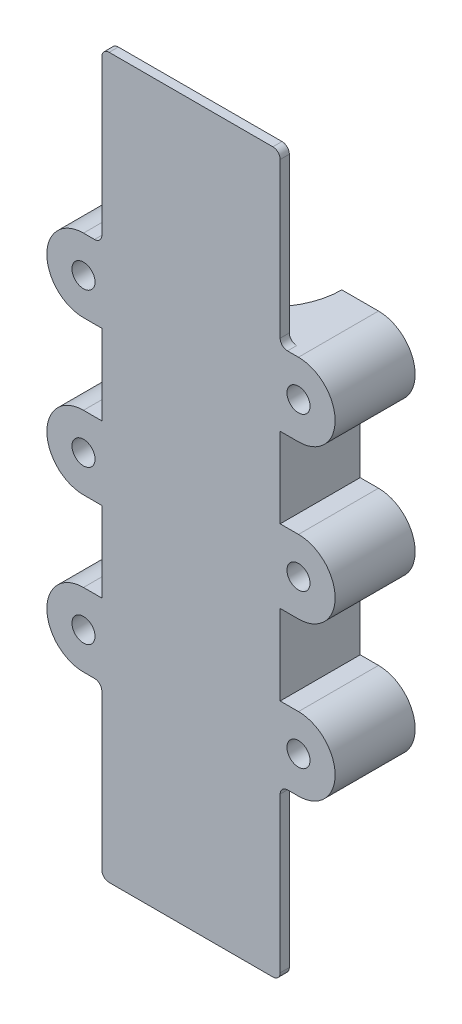
SolidWorks part; units mm, degrees
material "ABS"
ref_plane "X-Y Datum" through (0, 0, 0) normal (0, 0, 1) x (1, 0, 0)
ref_plane "X-Z Datum" through (0, 0, 0) normal (0, 1, 0) x (1, 0, 0)
ref_plane "Y-Z Datum" through (0, 0, 0) normal (1, 0, 0) x (0, 0, -1)
sketch "Sketch1" plane through (0, 0, 0) normal (0, 1, 0) x (1, 0, 0)
  line L0 (-12.2809, 0) -> (-15.4559, 0)
  line L1 (12.2809, 0) -> (15.4559, 0)
  line L4 (-15.4559, -13.3604) -> (-15.4559, 0)
  line L5 (15.4559, 0) -> (15.4559, -13.3604)
  line L10 (0, -13.8684) -> (15.4559, -13.8684)
  line L11 (15.4559, -13.8684) -> (15.4559, -13.3604)
  line L12 (-15.4559, -13.3604) -> (-15.4559, -13.8684)
  line L13 (-15.4559, -13.8684) -> (0, -13.8684)
  arc A0 (-12.2809, 0) -> (12.2809, 0) centre (0, 0) ccw
extrude "Boss-Extrude1" add sketch "Sketch1" along normal blind 65.8876
sketch "Sketch2" plane through (0, 65.8876, 0) normal (0, 1, 0) x (1, 0, 0)
  line L2 (-12.2809, -12.2809) -> (0, -12.2809)
  line L3 (0, -12.2809) -> (12.2809, -12.2809)
  line L6 (15.4559, -12.2809) -> (15.4559, -13.3604)
  line L8 (-15.4559, -13.3604) -> (-15.4559, -12.2809)
  line L9 (-12.2809, -12.2809) -> (-15.4559, -12.2809)
  line L10 (12.2809, -12.2809) -> (15.4559, -12.2809)
  line L13 (-15.4559, -13.3604) -> (-15.4559, -13.8684)
  line L14 (-15.4559, -13.8684) -> (15.4559, -13.8684)
  line L15 (15.4559, -13.8684) -> (15.4559, -13.3604)
  arc A0 (-12.2809, 0) -> (12.2809, 0) centre (0, 0) ccw construction
  point P0 (0, 0)
extrude "Boss-Extrude2" add sketch "Sketch2" along normal blind 29.3624
ref_plane "Plane1" through (0, 32.9438, 0) normal (0, 1, 0) x (1, 0, 0)
mirror "Mirror1" about plane through (0, 32.9438, 0) normal (0, 1, 0) of "Boss-Extrude2"
sketch "Sketch4" plane through (0, 0, 0) normal (0, 0, -1) x (-1, 0, 0)
  line L0 (-15.4559, 39.2938) -> (-15.4559, 26.5938)
  line L1 (-15.4559, 0) -> (-15.4559, 3.175) construction
  line L2 (8.5007, 32.9438) -> (-8.5007, 32.9438) construction
  line L3 (-18.6309, 39.2938) -> (-15.4559, 39.2938)
  line L4 (-18.6309, 26.5938) -> (-15.4559, 26.5938)
  line L5 (-15.4559, 65.8876) -> (-15.4559, 62.7126) construction
  line L6 (-15.4559, 65.8876) -> (-15.4559, 0) construction
  line L7 (-15.4559, 12.7) -> (-18.6309, 12.7)
  line L8 (-15.4559, 0) -> (-15.4559, 12.7)
  line L9 (-18.6309, 65.8876) -> (-15.4559, 65.8876)
  line L10 (-15.4559, 65.8876) -> (-15.4559, 53.1876)
  line L11 (-15.4559, 53.1876) -> (-18.6309, 53.1876)
  line L12 (0, 65.8876) -> (0, 56.8144) construction
  line L13 (-18.6309, 0) -> (-15.4559, 0)
  line L14 (15.4559, 65.8876) -> (15.4559, 62.7126) construction
  line L15 (15.4559, 0) -> (15.4559, 3.175) construction
  line L16 (18.6309, 0) -> (15.4559, 0)
  line L17 (15.4559, 53.1876) -> (18.6309, 53.1876)
  line L18 (15.4559, 65.8876) -> (15.4559, 53.1876)
  line L19 (18.6309, 65.8876) -> (15.4559, 65.8876)
  line L20 (15.4559, 0) -> (15.4559, 12.7)
  line L21 (15.4559, 12.7) -> (18.6309, 12.7)
  line L22 (18.6309, 26.5938) -> (15.4559, 26.5938)
  line L23 (18.6309, 39.2938) -> (15.4559, 39.2938)
  line L24 (15.4559, 39.2938) -> (15.4559, 26.5938)
  arc A0 (-18.6309, 39.2938) -> (-18.6309, 26.5938) centre (-18.6309, 32.9438) ccw
  arc A2 (-18.6309, 65.8876) -> (-18.6309, 53.1876) centre (-18.6309, 59.5376) ccw
  circle A3 centre (-18.6309, 59.5376) radius 2
  circle A4 centre (-18.6309, 32.9438) radius 2
  circle A5 centre (-18.6309, 6.35) radius 2
  arc A6 (-18.6309, 0) -> (-18.6309, 12.7) centre (-18.6309, 6.35) cw
  arc A7 (18.6309, 0) -> (18.6309, 12.7) centre (18.6309, 6.35) ccw
  circle A8 centre (18.6309, 6.35) radius 2
  circle A9 centre (18.6309, 32.9438) radius 2
  circle A10 centre (18.6309, 59.5376) radius 2
  arc A11 (18.6309, 65.8876) -> (18.6309, 53.1876) centre (18.6309, 59.5376) cw
  arc A12 (18.6309, 39.2938) -> (18.6309, 26.5938) centre (18.6309, 32.9438) cw
extrude "Boss-Extrude3" add sketch "Sketch4" against normal through all
fillet "Fillet1" radius 1.27 8 edges at (-15.4559, 65.8876, 13.0747) (-15.4559, 0, 13.0747) (15.4559, 95.25, 13.0747) (-15.4559, 95.25, 13.0747) (-15.4559, -29.3624, 13.0747) (15.4559, -29.3624, 13.0747) (15.4559, 65.8876, 13.0747) (15.4559, 0, 13.0747)
